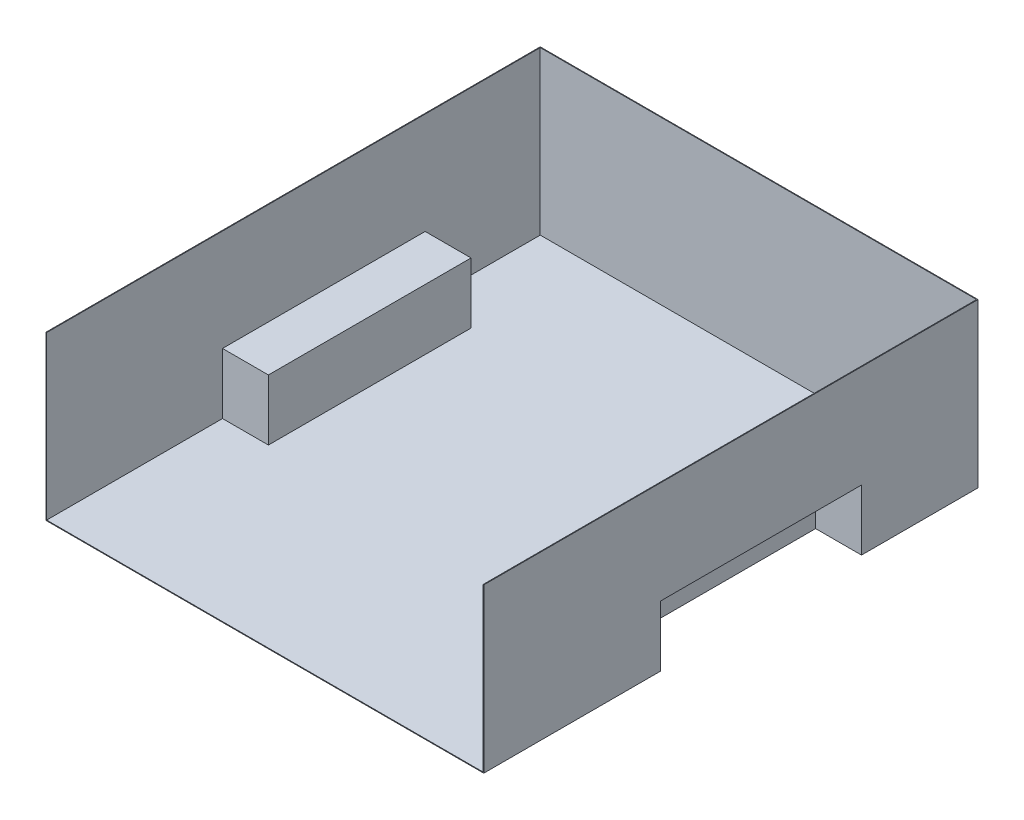
SolidWorks part; units mm, degrees
ref_plane "Front Plane" through (0, 0, 0) normal (0, 0, 1) x (1, 0, 0)
ref_plane "Top Plane" through (0, 0, 0) normal (0, 1, 0) x (1, 0, 0)
ref_plane "Right Plane" through (0, 0, 0) normal (1, 0, 0) x (0, 0, -1)
sketch "Sketch1" plane through (0, 0, 0) normal (0, 1, 0) x (1, 0, 0)
  line L0 (-787.4, 469.9) -> (-622.3, 469.9)
  line L1 (-787.4, -889) -> (787.4, -889)
  line L2 (-787.4, -889) -> (-787.4, -254)
  line L3 (-787.4, 889) -> (787.4, 889)
  line L4 (787.4, -889) -> (787.4, -254)
  line L5 (-787.4, -889) -> (787.4, 889) construction
  line L6 (-787.4, 889) -> (787.4, -889) construction
  line L7 (-622.3, 469.9) -> (-622.3, -254)
  line L8 (-622.3, -254) -> (-787.4, -254)
  line L9 (787.4, -254) -> (622.3, -254)
  line L10 (622.3, -254) -> (622.3, 469.9)
  line L11 (622.3, 469.9) -> (787.4, 469.9)
  line L12 (-787.4, 469.9) -> (-787.4, 889)
  line L13 (787.4, 469.9) -> (787.4, 889)
  point P0 (0, 0)
  dimension "D1" = 1778
  dimension "D2" = 1574.8
  dimension "D3" = 635
  dimension "D4" = 419.1
  dimension "D5" = 419.1
  dimension "D6" = 165.1
  dimension "D7" = 165.1
extrude "Extrude-Thin1" add sketch "Sketch1" along normal blind 215.9 thin thin type one direction reverse wall 2.54
sketch "Sketch4" plane through (0, 215.9, 0) normal (0, 1, 0) x (1, 0, 0)
  line L0 (-787.4, -254) -> (-787.4, -889) construction
  line L1 (-619.76, 472.44) -> (-787.4, 472.44)
  line L2 (-619.76, 472.44) -> (-619.76, -256.54)
  line L3 (-619.76, -256.54) -> (-787.4, -256.54)
  line L4 (-787.4, 472.44) -> (-787.4, -256.54)
  line L5 (787.4, -889) -> (787.4, -254) construction
  line L6 (619.76, 472.44) -> (787.4, 472.44)
  line L7 (619.76, 472.44) -> (619.76, -256.54)
  line L8 (619.76, -256.54) -> (787.4, -256.54)
  line L9 (787.4, 472.44) -> (787.4, -256.54)
extrude "Boss-Extrude3" add sketch "Sketch4" along normal blind 2.54
sketch "Sketch6" plane through (0, 215.9, 0) normal (0, 1, 0) x (1, 0, 0)
  line L0 (-784.86, 886.46) -> (-784.86, -886.46)
  line L1 (-787.4, 889) -> (787.4, 889)
  line L2 (-787.4, 889) -> (-787.4, -889)
  line L3 (-787.4, -889) -> (787.4, -889)
  line L4 (787.4, 889) -> (787.4, -889)
  line L5 (-784.86, -886.46) -> (784.86, -886.46)
  line L6 (784.86, 886.46) -> (784.86, -886.46)
  line L7 (-784.86, 886.46) -> (784.86, 886.46)
  dimension "D1" = 2.54
extrude "Boss-Extrude4" add sketch "Sketch6" along normal blind 368.3
sketch "Sketch7" plane through (0, 0, 0) normal (0, 1, 0) x (1, 0, 0)
  line L0 (0, 327.66) -> (-619.76, 327.66)
  line L1 (-619.76, 472.44) -> (-619.76, -256.54) construction
  line L2 (-619.76, 327.66) -> (-619.76, 480.06)
  line L3 (-619.76, 480.06) -> (-784.86, 645.16)
  line L4 (-784.86, 886.46) -> (-784.86, 472.44) construction
  line L5 (-784.86, 645.16) -> (-784.86, 886.46)
  line L6 (-784.86, 886.46) -> (784.86, 886.46)
  line L7 (784.86, 472.44) -> (784.86, 886.46) construction
  line L8 (784.86, 886.46) -> (-784.86, 886.46) construction
  line L9 (784.86, 886.46) -> (784.86, 645.16)
  line L10 (784.86, 645.16) -> (619.76, 480.06)
  line L11 (619.76, 480.06) -> (619.76, 327.66)
  line L12 (619.76, 327.66) -> (0, 327.66)
  line L13 (619.76, -256.54) -> (619.76, 472.44) construction
  line L14 (0, 340.36) -> (-607.06, 340.36)
  line L15 (-607.06, 340.36) -> (-607.06, 485.3205)
  line L16 (-607.06, 485.3205) -> (-772.16, 650.4205)
  line L17 (-772.16, 650.4205) -> (-772.16, 873.76)
  line L18 (-772.16, 873.76) -> (772.16, 873.76)
  line L19 (772.16, 873.76) -> (772.16, 650.4205)
  line L20 (772.16, 650.4205) -> (607.06, 485.3205)
  line L21 (607.06, 485.3205) -> (607.06, 340.36)
  line L22 (607.06, 340.36) -> (0, 340.36)
  point P4 (619.76, 403.0892)
  point P20 (-619.76, 563.7249)
  point P21 (619.76, 536.0771)
  point P22 (784.86, 679.45)
  dimension "D1" = 135
  dimension "D2" = 152.4
  dimension "D3" = 135
  dimension "D4" = 152.4
  dimension "D5" = 558.8
  dimension "D6" = 12.7
extrude "Boss-Extrude5" [suppressed] add sketch "Sketch7" along normal blind 254
sketch "Sketch8" plane through (0, 0, 0) normal (0, -1, 0) x (1, 0, 0)
  line L12 (787.4, -889) -> (787.4, -469.9)
  line L13 (787.4, -469.9) -> (622.3, -469.9)
  line L14 (622.3, -469.9) -> (622.3, 254)
  line L15 (622.3, 254) -> (787.4, 254)
  line L16 (787.4, 254) -> (787.4, 889)
  line L17 (787.4, 889) -> (-787.4, 889)
  line L18 (-787.4, 889) -> (-787.4, 254)
  line L19 (-787.4, 254) -> (-622.3, 254)
  line L20 (-622.3, 254) -> (-622.3, -469.9)
  line L21 (-622.3, -469.9) -> (-787.4, -469.9)
  line L22 (-787.4, -469.9) -> (-787.4, -889)
  line L23 (-787.4, -889) -> (787.4, -889)
  line L24 (787.4, -889) -> (787.4, -469.9)
  line L25 (787.4, -469.9) -> (622.3, -469.9)
  line L26 (622.3, -469.9) -> (622.3, 254)
  line L27 (622.3, 254) -> (787.4, 254)
  line L28 (787.4, 254) -> (787.4, 889)
  line L29 (787.4, 889) -> (-787.4, 889)
  line L30 (-787.4, 889) -> (-787.4, 254)
  line L31 (-787.4, 254) -> (-622.3, 254)
  line L32 (-622.3, 254) -> (-622.3, -469.9)
  line L33 (-622.3, -469.9) -> (-787.4, -469.9)
  line L34 (-787.4, -469.9) -> (-787.4, -889)
  line L35 (-787.4, -889) -> (787.4, -889)
  dimension "D1" = 0
extrude "Boss-Extrude6" add sketch "Sketch8" along normal blind 2.54
sketch "Sketch9" plane through (0, 584.2, 0) normal (0, 1, 0) x (1, 0, 0)
  line L0 (-787.4, -889) -> (787.4, -889) construction
  line L1 (-784.86, -886.46) -> (784.86, -886.46)
  line L2 (-784.86, -886.46) -> (-784.86, -889)
  line L3 (-784.86, -889) -> (784.86, -889)
  line L4 (784.86, -886.46) -> (784.86, -889)
extrude "Cut-Extrude1" cut sketch "Sketch9" against normal up to surface (584.2 mm away) up to face at (0, 0, -71.9667)
